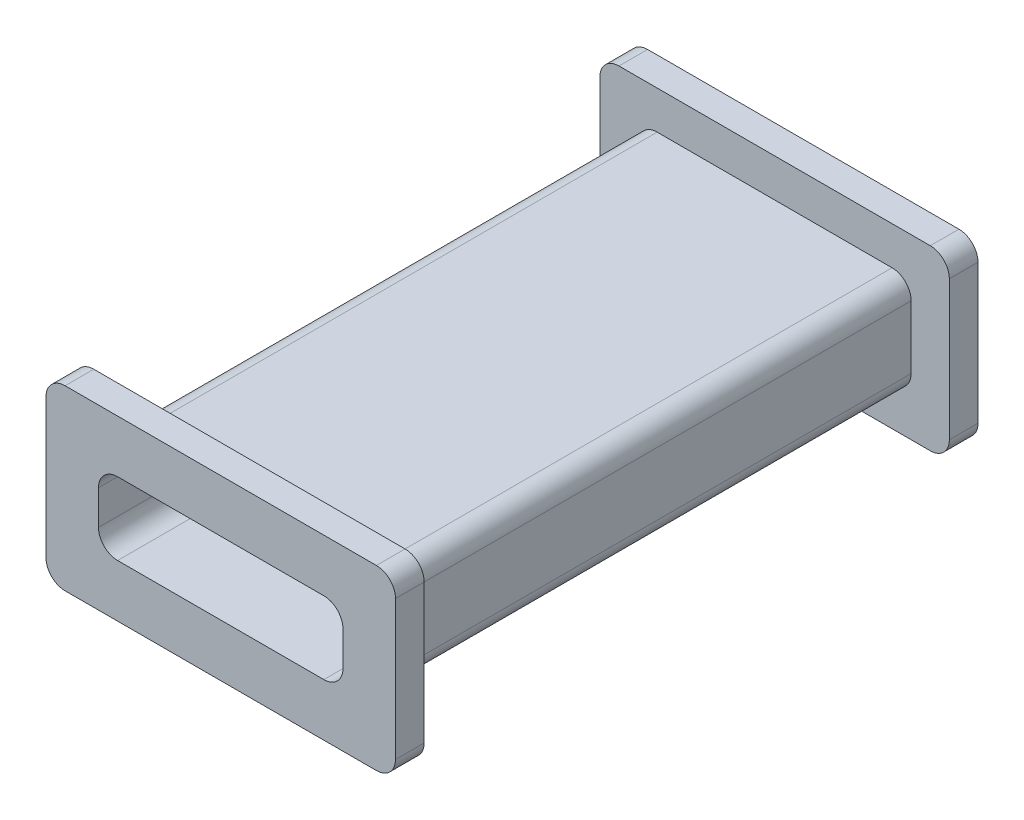
SolidWorks part; units mm, degrees
material "7079 Alloy"
ref_plane "Front Plane" through (0, 0, 0) normal (0, 0, 1) x (1, 0, 0)
ref_plane "Top Plane" through (0, 0, 0) normal (0, 1, 0) x (1, 0, 0)
ref_plane "Right Plane" through (0, 0, 0) normal (1, 0, 0) x (0, 0, -1)
sketch "Sketch1" plane through (0, 0, 0) normal (0, 0, 1) x (1, 0, 0)
  line L1 (-12.8, -3.8) -> (12.8, -3.8)
  line L2 (-12.8, -3.8) -> (-12.8, 3.8)
  line L3 (-12.8, 3.8) -> (12.8, 3.8)
  line L4 (12.8, -3.8) -> (12.8, 3.8)
  line L5 (-12.8, -3.8) -> (12.8, 3.8) construction
  line L6 (-12.8, 3.8) -> (12.8, -3.8) construction
  line L7 (-14.3, -5.3) -> (14.3, -5.3)
  line L8 (-14.3, -5.3) -> (-14.3, 5.3)
  line L9 (-14.3, 5.3) -> (14.3, 5.3)
  line L10 (14.3, -5.3) -> (14.3, 5.3)
  line L11 (-14.3, -5.3) -> (14.3, 5.3) construction
  line L12 (-14.3, 5.3) -> (14.3, -5.3) construction
  point P0 (0, 0)
  point P6 (0, 0)
  dimension "D1" = 1.5
  dimension "D2" = 1.5
  dimension "D3" = 10.6
  dimension "D4" = 25.6
extrude "Boss-Extrude1" add sketch "Sketch1" along normal blind 55
sketch "Sketch2" plane through (0, 0, 55) normal (0, 0, 1) x (1, 0, 0)
  line L0 (14.3, 5.3) -> (-14.3, 5.3) construction
  line L1 (-18.3, -9.3) -> (18.3, -9.3)
  line L2 (-18.3, -9.3) -> (-18.3, 9.3)
  line L3 (-18.3, 9.3) -> (18.3, 9.3)
  line L4 (18.3, -9.3) -> (18.3, 9.3)
  line L5 (-18.3, -9.3) -> (18.3, 9.3) construction
  line L6 (-18.3, 9.3) -> (18.3, -9.3) construction
  line L7 (-14.3, 5.3) -> (-14.3, -5.3) construction
  line L9 (-12.8, -3.8) -> (12.8, -3.8)
  line L10 (-12.8, -3.8) -> (-12.8, 3.8)
  line L11 (-12.8, 3.8) -> (12.8, 3.8)
  line L12 (12.8, -3.8) -> (12.8, 3.8)
  line L13 (-12.8, -3.8) -> (12.8, 3.8) construction
  line L14 (-12.8, 3.8) -> (12.8, -3.8) construction
  point P0 (0, 0)
  point P10 (0, 0)
  dimension "D1" = 4
  dimension "D2" = 4
extrude "Boss-Extrude3" add sketch "Sketch2" along normal blind 3
fillet "Fillet2" radius 2 4 edges at (-18.3, -9.3, 56.5) (18.3, -9.3, 56.5) (-18.3, 9.3, 56.5) (18.3, 9.3, 56.5)
sketch "Sketch3" plane through (0, 0, 58) normal (0, 0, 1) x (1, 0, 0)
  line L0 (-12.8, 3.8) -> (-12.8, -3.8) construction
  line L1 (-15.8, -6.3) -> (15.8, -6.3)
  line L2 (-15.8, -6.3) -> (-15.8, 6.3)
  line L3 (-15.8, 6.3) -> (15.8, 6.3)
  line L4 (15.8, -6.3) -> (15.8, 6.3)
  line L5 (-15.8, -6.3) -> (15.8, 6.3) construction
  line L6 (-15.8, 6.3) -> (15.8, -6.3) construction
  line L7 (-12.8, -3.8) -> (12.8, -3.8) construction
  line L8 (12.8, -3.8) -> (12.8, 3.8) construction
  line L9 (12.8, 3.8) -> (-12.8, 3.8) construction
  line L10 (-12.8, 3.8) -> (-12.8, -3.8)
  line L11 (-12.8, -3.8) -> (12.8, -3.8)
  line L12 (12.8, -3.8) -> (12.8, 3.8)
  line L13 (12.8, 3.8) -> (-12.8, 3.8)
  point P0 (0, 0)
  dimension "D1" = 2.5
  dimension "D2" = 3
ref_plane "Plane1" through (0, 0, 27.5) normal (0, 0, -1) x (-1, 0, 0)
fillet "Fillet1" radius 2 4 edges at (-14.3, -5.3, 27.5) (-14.3, 5.3, 27.5) (14.3, -5.3, 27.5) (14.3, 5.3, 27.5)
mirror "Mirror2" about plane through (0, 0, 27.5) normal (0, 0, -1) of "Fillet2", "Boss-Extrude3"
fillet "Fillet3" radius 2 4 edges at (12.8, -3.8, 27.5) (-12.8, -3.8, 27.5) (-12.8, 3.8, 27.5) (12.8, 3.8, 27.5)
